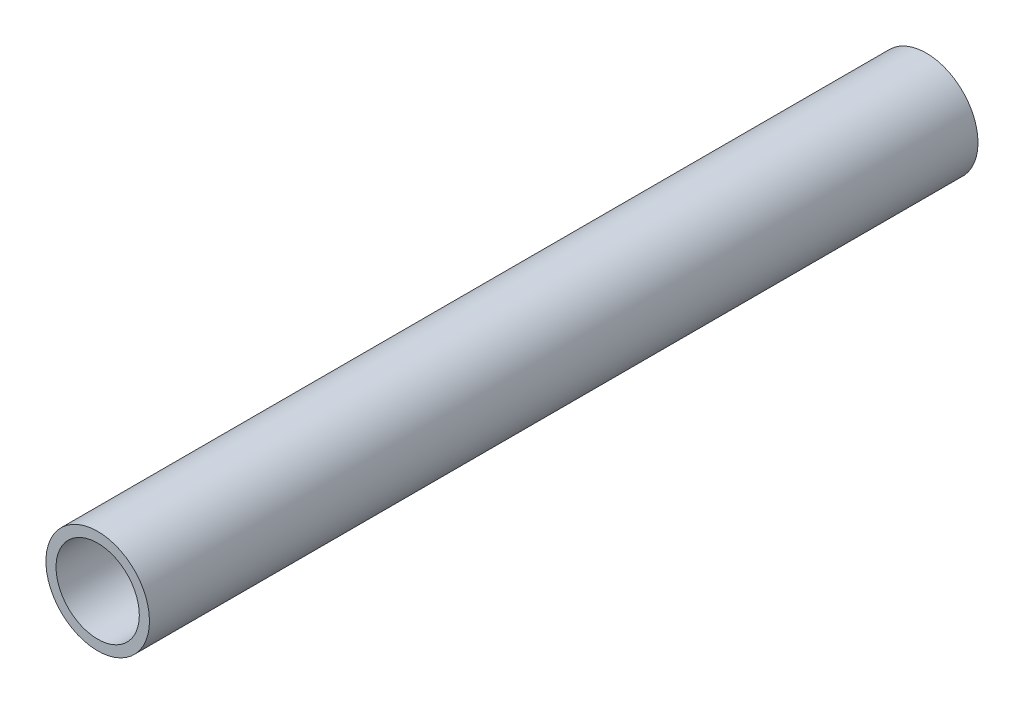
SolidWorks part; units mm, degrees
ref_plane "Front Plane" through (0, 0, 0) normal (0, 0, 1) x (1, 0, 0)
ref_plane "Top Plane" through (0, 0, 0) normal (0, 1, 0) x (1, 0, 0)
ref_plane "Right Plane" through (0, 0, 0) normal (1, 0, 0) x (0, 0, -1)
sketch "Sketch1" plane through (0, 0, 0) normal (0, 0, 1) x (1, 0, 0)
  circle A0 centre (0, 0) radius 3.175
  circle A1 centre (0, 0) radius 2.5527
  dimension "D1" = 5.1054
  dimension "D2" = 6.35
extrude "Boss-Extrude1" add sketch "Sketch1" along normal mid plane 50.8
